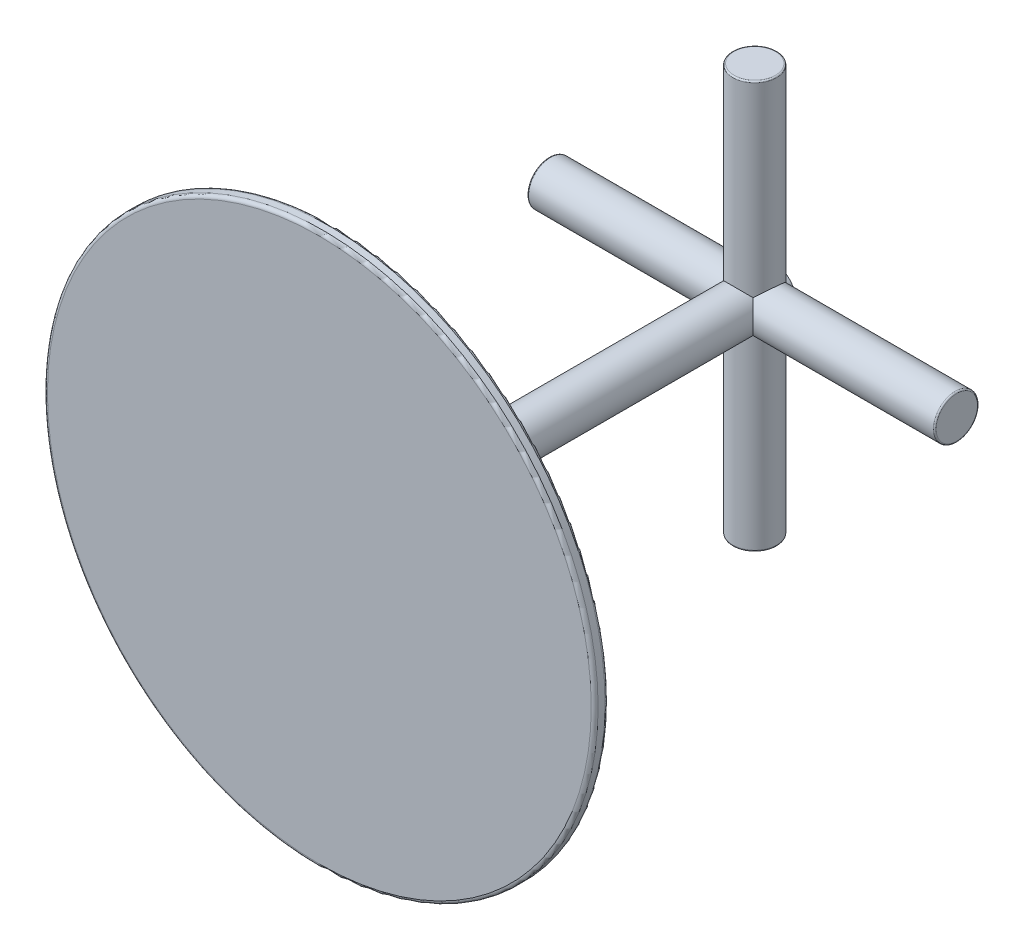
SolidWorks part; units mm, degrees
material "PW100:Mi:0:41:Ar:0:-1:C1:1:2:3:Re:15:"
ref_plane "Plane1" through (0, 0, 0) normal (0, 0, 1) x (1, 0, 0)
ref_plane "Plane2" through (0, 0, 0) normal (0, 1, 0) x (1, 0, 0)
ref_plane "Plane3" through (0, 0, 0) normal (1, 0, 0) x (0, 0, -1)
other "Configuration Table"
sketch "Sketch1" plane through (0, 0, 0) normal (0, 0, 1) x (1, 0, 0)
  circle A0 centre (0, 0) radius 508
  dimension "D1" = 1016
extrude "Base-Extrude" add sketch "Sketch1" along normal blind 25.4
sketch "Sketch5" plane through (0, 0, 0) normal (0, 0, -1) x (-1, 0, 0)
  circle A0 centre (0, 0) radius 40.64
  dimension "D1" = 81.28
extrude "Boss-Extrude1" add sketch "Sketch5" along normal blind 812.8
sketch "Sketch6" plane through (0, 0, 0) normal (1, 0, 0) x (0, 0, -1)
  line L0 (-25.4, 0) -> (0, 0) construction
  circle A1 centre (774.7102, 0) radius 40.64
extrude "Boss-Extrude2" add sketch "Sketch6" along normal mid plane 751.84
sketch "Sketch7" plane through (0, 0, 0) normal (0, 1, 0) x (1, 0, 0)
  circle A0 centre (0, 777.8878) radius 40.64
  dimension "D1" = 81.28
extrude "Boss-Extrude3" add sketch "Sketch7" along normal mid plane 751.84
fillet "Fillet2" radius 6.35 2 edges at (508, 0, 0) (508, 0, 25.4)
fillet "Fillet3" radius 2.54 4 edges at (-375.92, 0, -815.3502) (375.92, 0, -815.3502) (0, -375.92, -737.2478) (0, 375.92, -737.2478)
